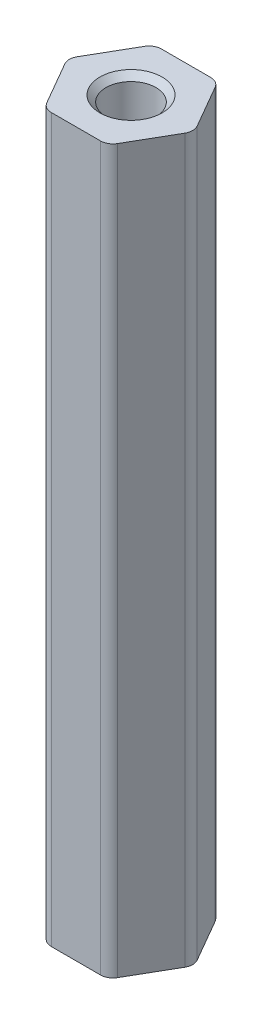
SolidWorks part; units mm, degrees
material "Brass"
ref_plane "Front Plane" through (0, 0, 0) normal (0, 0, 1) x (1, 0, 0)
ref_plane "Top Plane" through (0, 0, 0) normal (0, 1, 0) x (1, 0, 0)
ref_plane "Right Plane" through (0, 0, 0) normal (1, 0, 0) x (0, 0, -1)
sketch "Sketch1" plane through (0, 0, 0) normal (0, 1, 0) x (1, 0, 0)
  line L0 (0, 0) -> (2.6035, 0) construction
  line L1 (0, 0) -> (-2.6035, 0) construction
  line L2 (0, 0) -> (-1.3017, 2.2547) construction
  line L3 (0, 0) -> (1.3017, -2.2547) construction
  line L4 (0, 0) -> (1.3017, 2.2547) construction
  line L5 (0, 0) -> (-1.3017, -2.2547) construction
  line L6 (-2.6035, 0) -> (-1.3017, 2.2547)
  line L7 (-1.3017, 2.2547) -> (1.3017, 2.2547)
  line L8 (1.3017, 2.2547) -> (2.6035, 0)
  line L9 (2.6035, 0) -> (1.3017, -2.2547)
  line L10 (1.3017, -2.2547) -> (-1.3017, -2.2547)
  line L11 (-1.3017, -2.2547) -> (-2.6035, 0)
  dimension "D1" = 5.207
  dimension "D2" = 60
  dimension "D3" = 60
extrude "Boss-Extrude1" add sketch "Sketch1" along normal blind 29.591 contours L7 L8 L9 L10 L11 L6
fillet "Fillet1" radius 0.508 6 edges at (-2.6035, 14.7955, 0) (-1.3017, 14.7955, 2.2547) (-1.3017, 14.7955, -2.2547) (1.3017, 14.7955, -2.2547) (2.6035, 14.7955, 0) (1.3017, 14.7955, 2.2547)
sketch "Sketch3" plane through (0, 29.591, 0) normal (0, 1, 0) x (1, 0, 0)
  circle A0 centre (0, 0) radius 1.27
  dimension "D1" = 2.54
hole_wizard "M2.5x0.45 Tapped Hole1" positions "3DSketch1" profile "Sketch4" tap size "M2.5x0.45" standard "ANSI Metric" end condition through all
sketch3d "3DSketch1"
  point P0 (0, 29.591, 0)
sketch "Sketch4" plane through (0, 29.591, 0) normal (1, 0, 0) x (0, 0, 1)
  line L0 (0, 0) -> (0, 29.591)
  line L1 (0, 29.591) -> (1.025, 29.591)
  line L2 (1.025, 29.591) -> (1.025, 0.25)
  line L3 (1.025, 0.25) -> (1.275, 0)
  line L5 (1.275, 0) -> (0, 0)
  line L6 (-1.025, 0.25) -> (-1.275, 0) construction
  line L11 (0, -6.35) -> (0, 107.95) construction
  dimension "Thru Tap Drill Dia." = 2.05
  dimension "Thru Tap Drill Depth" = 29.591
  dimension "Near C'Sink Dia." = 2.55
  dimension "Near C'Sink Angle" = 90
